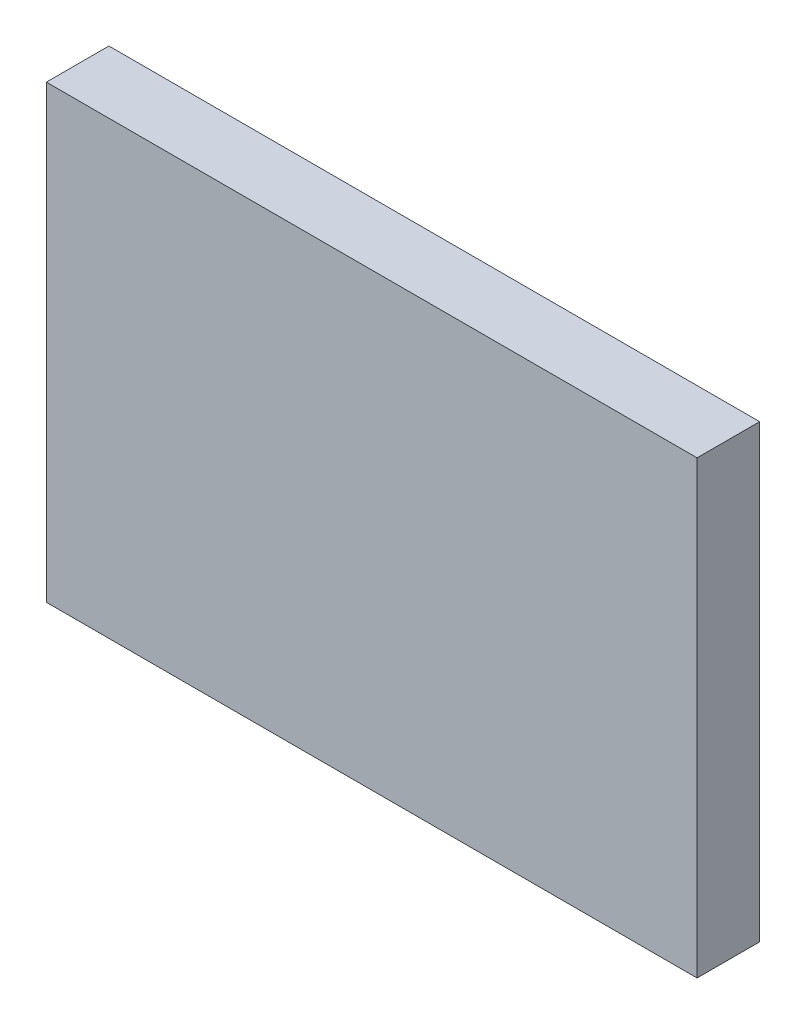
SolidWorks part; units mm, degrees
ref_plane "Front Plane" through (0, 0, 0) normal (0, 0, 1) x (1, 0, 0)
ref_plane "Top Plane" through (0, 0, 0) normal (0, 1, 0) x (1, 0, 0)
ref_plane "Right Plane" through (0, 0, 0) normal (1, 0, 0) x (0, 0, -1)
sketch "Sketch1" plane through (0, 0, 0) normal (0, 1, 0) x (1, 0, 0)
  line L1 (0, 0) -> (26, 0)
  line L2 (0, 0) -> (0, 2.5)
  line L3 (0, 2.5) -> (26, 2.5)
  line L4 (26, 0) -> (26, 2.5)
  dimension "D1" = 26
  dimension "D2" = 2.5
extrude "Boss-Extrude1" add sketch "Sketch1" along normal blind 18
